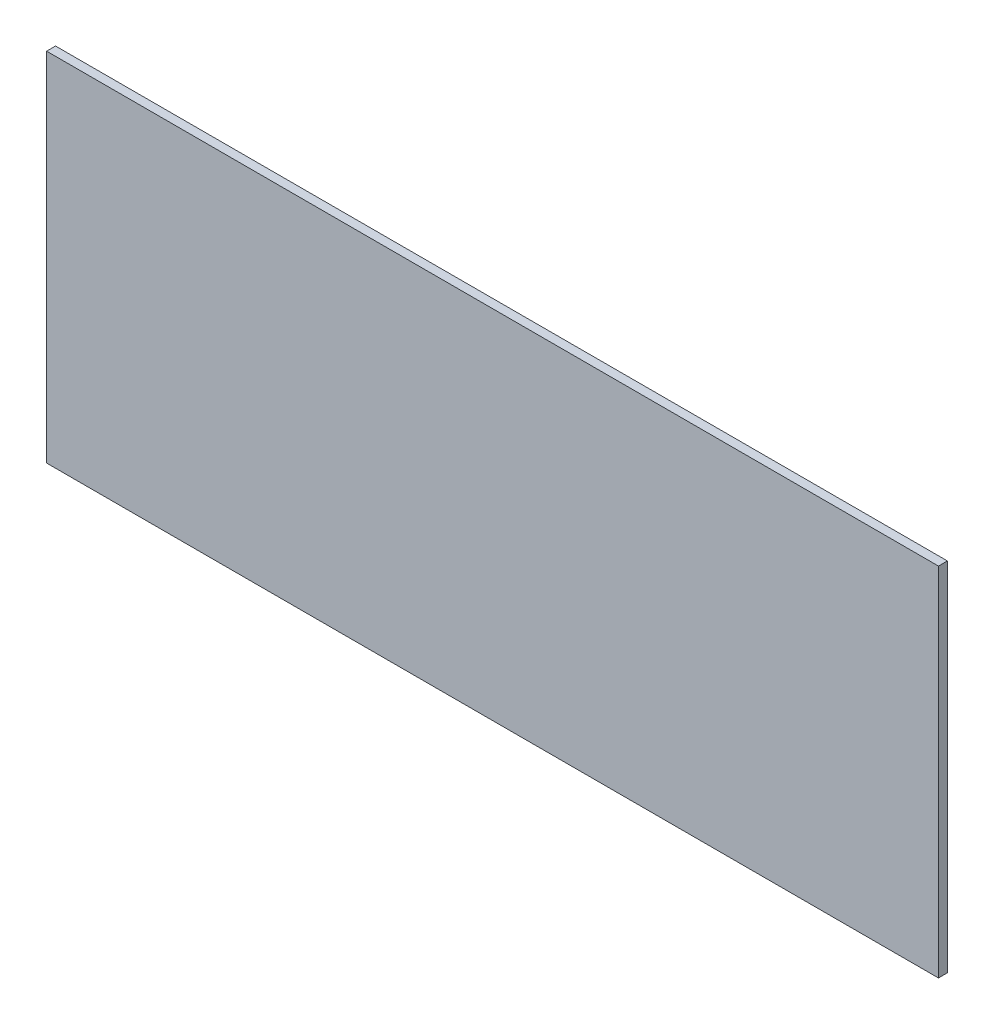
SolidWorks part; units mm, degrees
ref_plane "Front Plane" through (0, 0, 0) normal (0, 0, 1) x (1, 0, 0)
ref_plane "Top Plane" through (0, 0, 0) normal (0, 1, 0) x (1, 0, 0)
ref_plane "Right Plane" through (0, 0, 0) normal (1, 0, 0) x (0, 0, -1)
sketch "Sketch1" plane through (0, 0, 0) normal (0, 0, 1) x (1, 0, 0)
  line L1 (0, 0) -> (254, 0)
  line L2 (0, 0) -> (0, 101.6)
  line L3 (0, 101.6) -> (254, 101.6)
  line L4 (254, 0) -> (254, 101.6)
  dimension "D1" = 101.6
  dimension "D2" = 254
extrude "Boss-Extrude1" add sketch "Sketch1" along normal blind 2.54
